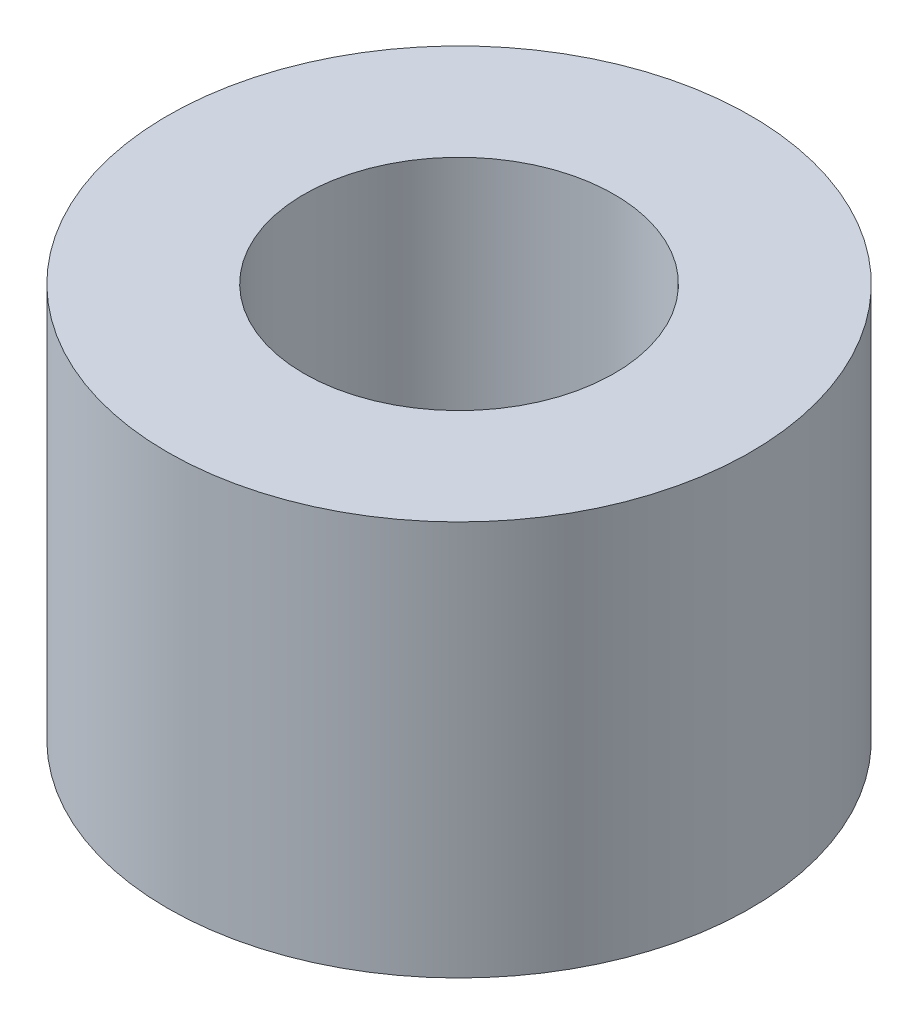
SolidWorks part; units mm, degrees
ref_plane "Front Plane" through (0, 0, 0) normal (0, 0, 1) x (1, 0, 0)
ref_plane "Top Plane" through (0, 0, 0) normal (0, 1, 0) x (1, 0, 0)
ref_plane "Right Plane" through (0, 0, 0) normal (1, 0, 0) x (0, 0, -1)
sketch "Sketch1" plane through (0, 0, 0) normal (0, 1, 0) x (1, 0, 0)
  circle A0 centre (0, 0) radius 1.65
  circle A1 centre (0, 0) radius 3.1
  dimension "D1" = 3.3
  dimension "D2" = 6.2
extrude "Boss-Extrude1" add sketch "Sketch1" along normal blind 4.2
